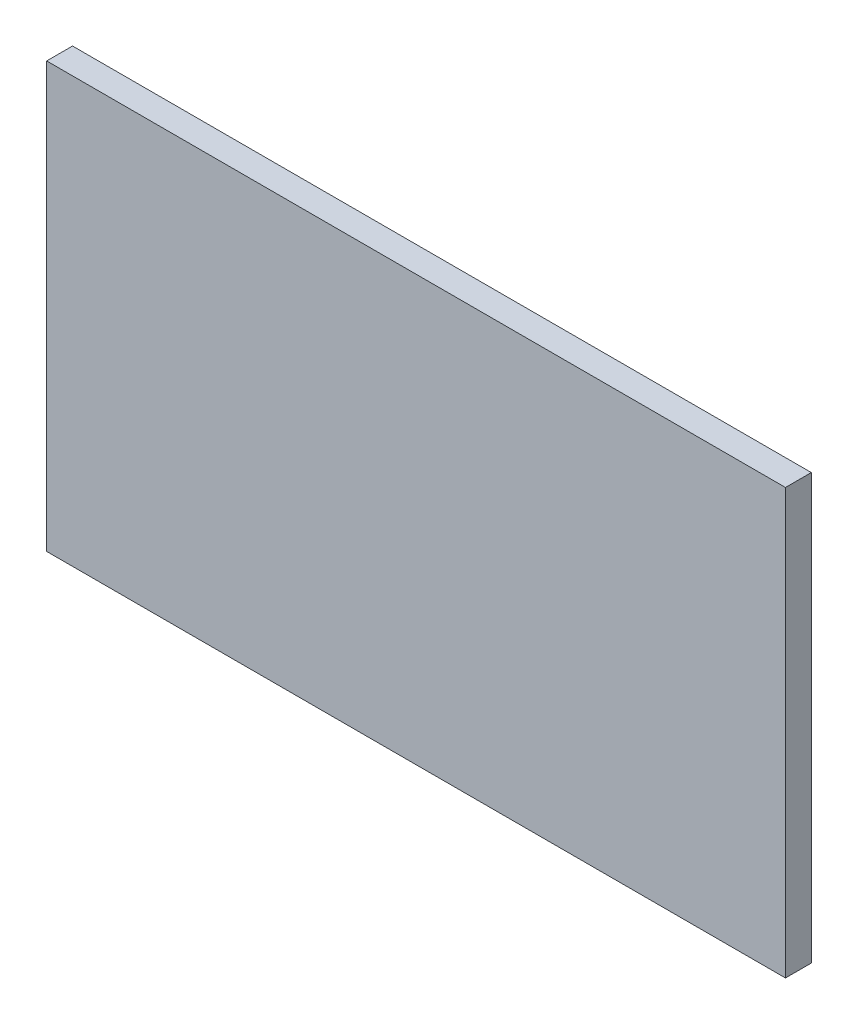
SolidWorks part; units mm, degrees
ref_plane "Front Plane" through (0, 0, 0) normal (0, 0, 1) x (1, 0, 0)
ref_plane "Top Plane" through (0, 0, 0) normal (0, 1, 0) x (1, 0, 0)
ref_plane "Right Plane" through (0, 0, 0) normal (1, 0, 0) x (0, 0, -1)
sketch "Sketch1" plane through (0, 0, 0) normal (0, 0, 1) x (1, 0, 0)
  line L1 (-254, 146.05) -> (254, 146.05)
  line L2 (-254, 146.05) -> (-254, -146.05)
  line L3 (-254, -146.05) -> (254, -146.05)
  line L4 (254, 146.05) -> (254, -146.05)
  line L5 (-254, 146.05) -> (254, -146.05) construction
  line L6 (-254, -146.05) -> (254, 146.05) construction
  point P0 (0, 0)
  dimension "D1" = 508
  dimension "D2" = 292.1
extrude "Boss-Extrude1" add sketch "Sketch1" along normal blind 17.78
